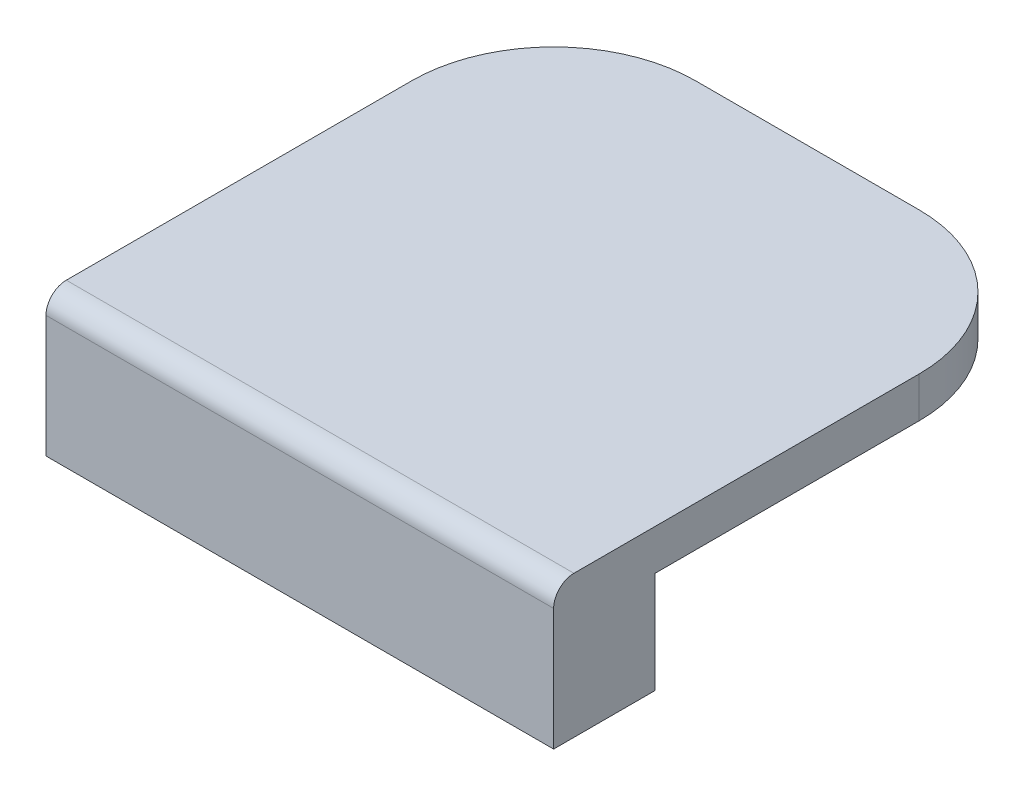
SolidWorks part; units mm, degrees
material "Beryllium"
ref_plane "Front Plane" through (0, 0, 0) normal (0, 0, 1) x (1, 0, 0)
ref_plane "Top Plane" through (0, 0, 0) normal (0, 1, 0) x (1, 0, 0)
ref_plane "Right Plane" through (0, 0, 0) normal (1, 0, 0) x (0, 0, -1)
sketch "Sketch1" plane through (0, 0, 0) normal (0, 1, 0) x (1, 0, 0)
  line L1 (-55, 125) -> (55, 125)
  line L2 (-125, 55) -> (-125, -125)
  line L3 (-125, -125) -> (125, -125)
  line L4 (125, 55) -> (125, -125)
  line L5 (-125, 125) -> (125, -125) construction
  line L6 (-125, -125) -> (125, 125) construction
  arc A0 (55, 125) -> (125, 55) centre (55, 55) cw
  arc A1 (-55, 125) -> (-125, 55) centre (-55, 55) ccw
  point P0 (0, 0)
  dimension "D3" = 70
  dimension "D1" = 250
  dimension "D2" = 250
extrude "Boss-Extrude1" add sketch "Sketch1" along normal blind 20
sketch "Sketch2" plane through (0, 0, 0) normal (0, -1, 0) x (1, 0, 0)
  line L0 (125, 125) -> (125, -55) construction
  line L1 (-125, 125) -> (125, 125)
  line L2 (-125, 125) -> (-125, 75)
  line L3 (-125, 75) -> (125, 75)
  line L4 (125, 125) -> (125, 75)
  dimension "D1" = 50
extrude "Boss-Extrude2" add sketch "Sketch2" along normal blind 50
ref_plane "Plane1" through (0, 0, 0) normal (1, 0, 0) x (0, 0, -1)
ref_point "Point1"
fillet "Fillet1" radius 10 1 edges at (0, 20, 125)
sketch "Sketch3" plane through (0, 0, 0) normal (0, -1, 0) x (1, 0, 0)
  line L0 (-55, -125) -> (55, -125)
  line L1 (-55, -125) -> (-55, -65)
  line L2 (55, -125) -> (55, -65)
  line L3 (-55, -65) -> (55, -65)
  arc A0 (-125, -55) -> (-55, -125) centre (-55, -55) ccw construction
  dimension "D1" = 60
